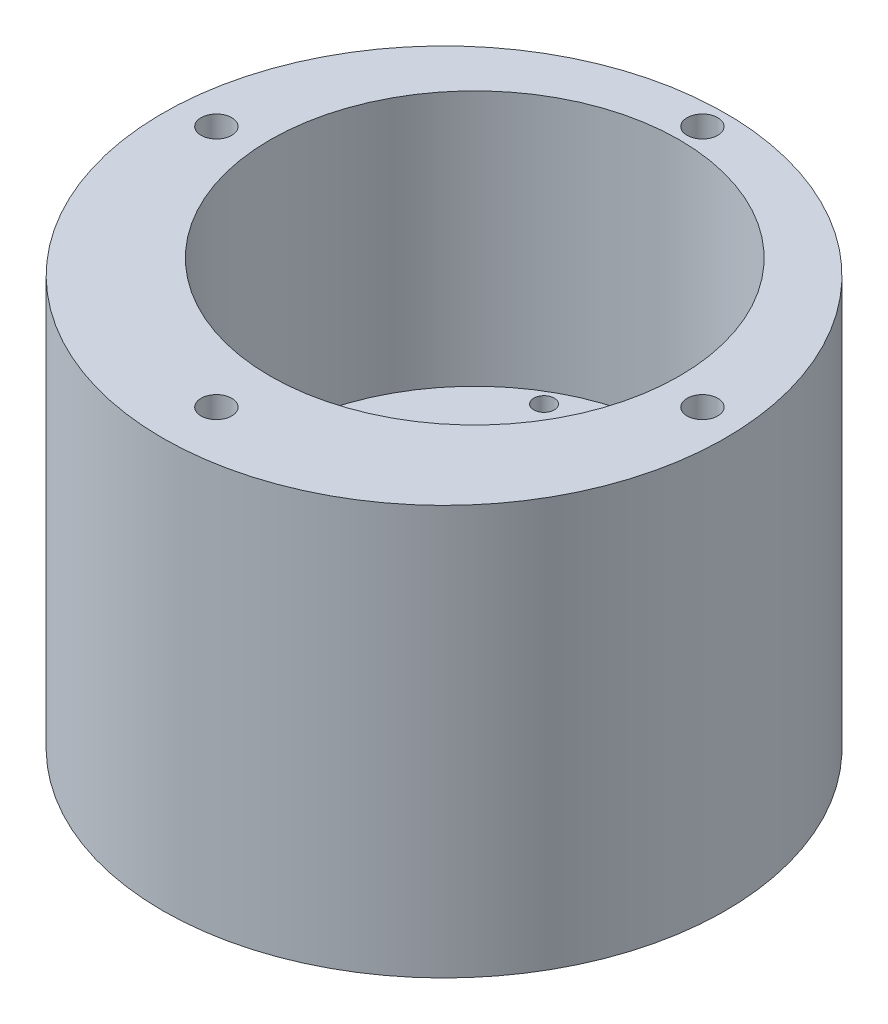
SolidWorks part; units mm, degrees
ref_plane "Front Plane" through (0, 0, 0) normal (0, 0, 1) x (1, 0, 0)
ref_plane "Top Plane" through (0, 0, 0) normal (0, 1, 0) x (1, 0, 0)
ref_plane "Right Plane" through (0, 0, 0) normal (1, 0, 0) x (0, 0, -1)
sketch "Sketch1" plane through (0, 0, 0) normal (0, 1, 0) x (1, 0, 0)
  line L0 (10, 17.3205) -> (9.25, 16.0215) construction
  line L1 (-9.25, 16.0215) -> (9.25, 16.0215) construction
  line L2 (0, 20) -> (0, 0) construction
  line L3 (9.25, -16.0215) -> (10, -17.3205) construction
  circle A0 centre (0, 0) radius 20
  circle A1 centre (0, 10) radius 10
  circle A2 centre (9.25, 16.0215) radius 1
  circle A3 centre (18.5, 0) radius 1
  circle A4 centre (9.25, -16.0215) radius 1
  circle A5 centre (-9.25, -16.0215) radius 1
  circle A6 centre (-18.5, 0) radius 1
  circle A7 centre (-9.25, 16.0215) radius 1
  circle A8 centre (0, -3) radius 27.5
  point P23 (0, 16.0215)
  dimension "D1" = 40
  dimension "D2" = 20
  dimension "D3" = 2
  dimension "D7" = 55
  dimension "D4" = 1.5
  dimension "D6" = 1.5
  dimension "D8" = 3
  dimension "D5" = 6
extrude "Boss-Extrude2" add sketch "Sketch1" along normal blind 15 contours A0 A8 | A0 A1 A7 A6 A5 A4 A3 A2 | A1
sketch "Sketch2" plane through (0, 15, 0) normal (0, 1, 0) x (1, 0, 0)
  circle A0 centre (0, 10) radius 9
  circle A1 centre (0, 10) radius 10 construction
  dimension "D1" = 18
extrude "Cut-Extrude17" cut sketch "Sketch2" against normal through all both and the other way through all
ref_plane "Plane2" through (0, 15, 0) normal (0, 1, 0) x (1, 0, 0)
sketch "Sketch7" plane through (0, 15, 0) normal (0, 1, 0) x (1, 0, 0)
  circle A0 centre (0, 0) radius 20
  circle A1 centre (0, -3) radius 27.5
  circle A2 centre (0, 0) radius 20 construction
  circle A3 centre (0, -3) radius 27.5 construction
extrude "Boss-Extrude4" add sketch "Sketch7" along normal blind 25 contours A1 | A0
sketch "Sketch8" plane through (0, 40, 0) normal (0, 1, 0) x (1, 0, 0)
  line L0 (0, 24.5) -> (0, 20) construction
  line L1 (0, -20) -> (0, -30.5) construction
  circle A0 centre (0, 22.25) radius 1.5
  circle A1 centre (0, -3) radius 27.5 construction
  circle A2 centre (0, 0) radius 20 construction
  circle A3 centre (23.75, -1.5) radius 1.5
  circle A4 centre (0, -25.25) radius 1.5
  circle A5 centre (-23.75, -1.5) radius 1.5
  circle A6 centre (0, 0) radius 20 construction
  point P2 (0, 0)
  point P20 (0, 0)
  point P21 (0, 0)
  dimension "D1" = 3
  dimension "D2" = 4
extrude "Cut-Extrude18" cut sketch "Sketch8" against normal through all both and the other way through all
